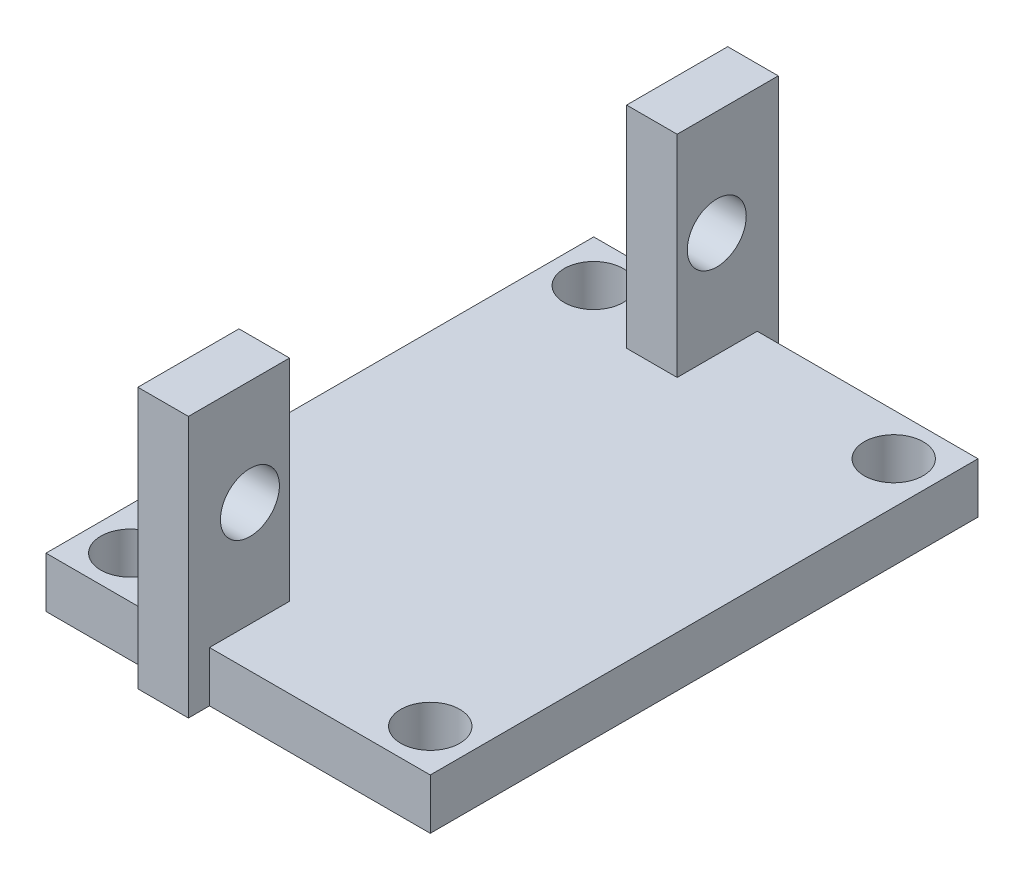
SolidWorks part; units mm, degrees
ref_plane "前视基准面" through (0, 0, 0) normal (0, 0, 1) x (1, 0, 0)
ref_plane "上视基准面" through (0, 0, 0) normal (0, 1, 0) x (1, 0, 0)
ref_plane "右视基准面" through (0, 0, 0) normal (1, 0, 0) x (0, 0, -1)
sketch "草图1" plane through (0, 0, 0) normal (0, 1, 0) x (1, 0, 0)
  line L1 (-11.4, 16.25) -> (11.4, 16.25)
  line L2 (-11.4, 16.25) -> (-11.4, -16.25)
  line L3 (-11.4, -16.25) -> (11.4, -16.25)
  line L4 (11.4, 16.25) -> (11.4, -16.25)
  line L5 (-11.4, 16.25) -> (11.4, -16.25) construction
  line L6 (-11.4, -16.25) -> (11.4, 16.25) construction
  point P0 (0, 0)
  dimension "D1" = 32.5
  dimension "D2" = 22.8
extrude "凸台-拉伸1" add sketch "草图1" along normal blind 3
sketch "草图4" plane through (0, 3, 0) normal (0, 1, 0) x (1, 0, 0)
  line L1 (-8.9, 13.75) -> (8.9, 13.75) construction
  line L2 (-8.9, 13.75) -> (-8.9, -13.75) construction
  line L3 (-8.9, -13.75) -> (8.9, -13.75) construction
  line L4 (8.9, 13.75) -> (8.9, -13.75) construction
  line L5 (-11.4, 16.25) -> (-11.4, -16.25) construction
  line L6 (11.4, 16.25) -> (-11.4, 16.25) construction
  line L7 (-11.4, -16.25) -> (11.4, -16.25) construction
  line L8 (11.4, -16.25) -> (11.4, 16.25) construction
  circle A0 centre (-8.9, 13.75) radius 1.75
  circle A1 centre (8.9, 13.75) radius 1.75
  circle A2 centre (-8.9, -13.75) radius 1.75
  circle A3 centre (8.9, -13.75) radius 1.75
  dimension "D5" = 3.5
  dimension "D6" = 3.5
  dimension "D7" = 3.5
  dimension "D8" = 3.5
  dimension "D1" = 2.5
  dimension "D2" = 2.5
  dimension "D3" = 2.5
  dimension "D4" = 2.5
  dimension "D10" = 17.8
extrude "切除-拉伸2" cut sketch "草图4" against normal blind 10
sketch "草图2" plane through (0, 3, 0) normal (0, 1, 0) x (1, 0, 0)
  line L1 (-4.7, -17.5) -> (-1.7, -17.5)
  line L2 (-4.7, -17.5) -> (-4.7, -11.5)
  line L3 (-4.7, -11.5) -> (-1.7, -11.5)
  line L4 (-1.7, -17.5) -> (-1.7, -11.5)
  line L6 (-1.7, 17.5) -> (-4.7, 17.5)
  line L7 (-1.7, 17.5) -> (-1.7, 11.5)
  line L8 (-1.7, 11.5) -> (-4.7, 11.5)
  line L9 (-4.7, 17.5) -> (-4.7, 11.5)
  line L10 (11.4, -16.25) -> (11.4, 16.25) construction
  line L12 (-11.4, 0) -> (11.4, 0) construction
  line L13 (-11.4, 16.25) -> (-11.4, -16.25) construction
  line L14 (-11.4, 11.5) -> (11.4, 11.5) construction
  line L15 (-11.4, -11.5) -> (11.4, -11.5) construction
  circle A0 centre (8.9, -13.75) radius 1.75 construction
  circle A1 centre (-8.9, -13.75) radius 1.75 construction
  circle A2 centre (8.9, 13.75) radius 1.75 construction
  circle A3 centre (-8.9, 13.75) radius 1.75 construction
  circle A4 centre (8.9, -13.75) radius 1.75 construction
  circle A5 centre (-8.9, -13.75) radius 1.75 construction
  circle A6 centre (8.9, 13.75) radius 1.75 construction
  circle A7 centre (-8.9, 13.75) radius 1.75 construction
  dimension "D1" = 16.1
  dimension "D2" = 3
  dimension "D3" = 23
  dimension "D4" = 35
extrude "凸台-拉伸2" add sketch "草图2" along normal blind 15.5 from surface at -3 starting at face at (8.9, 0, -12)
sketch "草图3" plane through (-1.7, 0, 0) normal (1, 0, 0) x (0, 0, -1)
  line L0 (-11.5, 9.25) -> (11.5, 9.25) construction
  line L1 (-11.5, 15.5) -> (-11.5, 3) construction
  line L2 (11.5, 15.5) -> (11.5, 3) construction
  line L3 (13.85, 9.25) -> (-13.85, 9.25) construction
  circle A0 centre (-13.85, 9.25) radius 1.75
  circle A1 centre (13.85, 9.25) radius 1.75
  point P9 (0, 9.25)
  dimension "D2" = 3.5
  dimension "D3" = 3.5
  dimension "D1" = 27.7
extrude "切除-拉伸1" cut sketch "草图3" against normal through all
